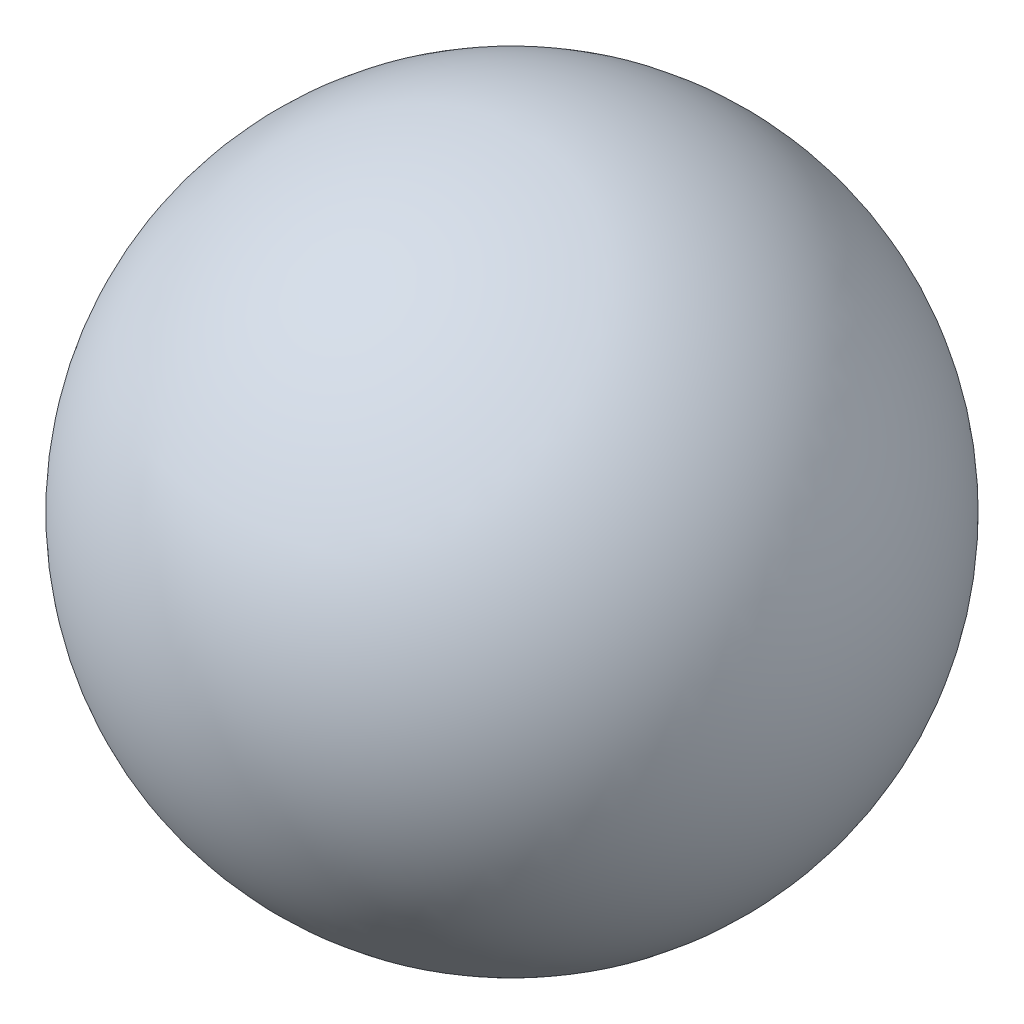
SolidWorks part; units mm, degrees
ref_plane "Front Plane" through (0, 0, 0) normal (0, 0, 1) x (1, 0, 0)
ref_plane "Top Plane" through (0, 0, 0) normal (0, 1, 0) x (1, 0, 0)
ref_plane "Right Plane" through (0, 0, 0) normal (1, 0, 0) x (0, 0, -1)
sketch "Sketch2" plane through (26.5, 0, 0) normal (-1, 0, 0) x (0, 0, 1)
  line L1 (-50, 66.6273) -> (-50, -103.3727)
  line L2 (24.75, -18.3727) -> (-24.75, -18.3727) construction
  arc A0 (-50, 66.6273) -> (-50, -103.3727) centre (-50, -18.3727) cw
  point P0 (-50, -18.3727)
  dimension "D1" = 85
  dimension "D2" = 50
revolve "Revolve1" add sketch "Sketch2" angle 360 about L1
